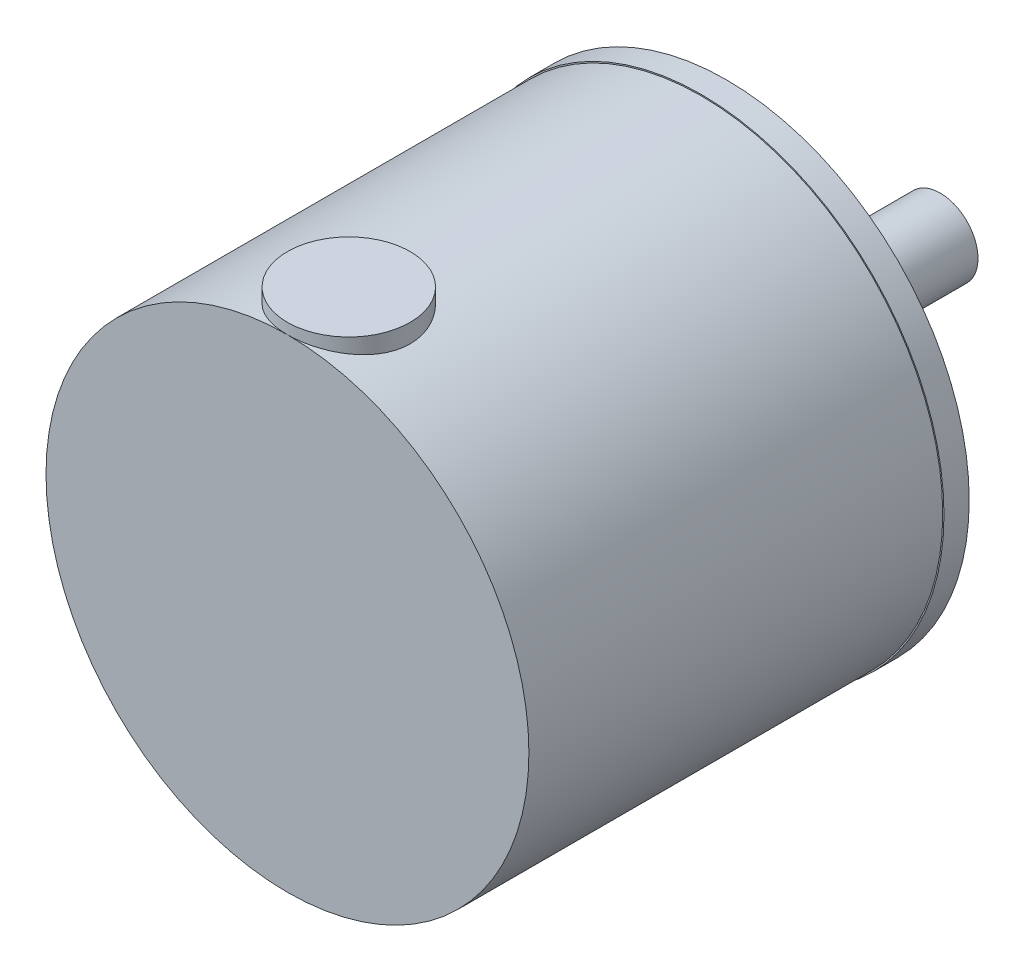
SolidWorks part; units mm, degrees
ref_plane "Alzado" through (0, 0, 0) normal (0, 0, 1) x (1, 0, 0)
ref_plane "Planta" through (0, 0, 0) normal (0, 1, 0) x (1, 0, 0)
ref_plane "Vista lateral" through (0, 0, 0) normal (1, 0, 0) x (0, 0, -1)
sketch "Croquis1" plane through (0, 0, 0) normal (0, 0, 1) x (1, 0, 0)
  circle A0 centre (0, 0) radius 19.15
  dimension "D1" = 38.3
extrude "Saliente-Extruir1" add sketch "Croquis1" along normal blind 34.82
sketch "Croquis2" plane through (0, 0, 0) normal (0, 0, -1) x (-1, 0, 0)
  circle A0 centre (0, 0) radius 9.975
  dimension "D1" = 19.95
extrude "Saliente-Extruir2" add sketch "Croquis2" along normal blind 4.95
sketch "Croquis3" plane through (0, 0, -4.95) normal (0, 0, -1) x (-1, 0, 0)
  line L0 (-1.8393, -2.37) -> (1.8393, -2.37)
  arc A0 (1.8393, -2.37) -> (-1.8393, -2.37) centre (0, 0) ccw
  dimension "D1" = 6
  dimension "D2" = 2.37
extrude "Saliente-Extruir3" add sketch "Croquis3" along normal blind 12
sketch "Croquis4" plane through (0, 0, 0) normal (0, 1, 0) x (1, 0, 0)
  line L0 (-19.15, -34.82) -> (19.15, -34.82) construction
  circle A0 centre (0, -29.955) radius 4.865
  dimension "D1" = 9.73
extrude "Saliente-Extruir4" add sketch "Croquis4" along normal blind 20
sketch "Croquis5" plane through (0, 0, 0) normal (0, 0, -1) x (-1, 0, 0)
  circle A0 centre (0, 0) radius 19.25
  circle A1 centre (0, 0) radius 19.15 construction
  dimension "D1" = 0.1
extrude "Saliente-Extruir5" add sketch "Croquis5" against normal blind 2
sketch "Croquis6" plane through (0, 0, 0) normal (0, 0, -1) x (-1, 0, 0)
  line L0 (-2.6494, -14.1885) -> (13.6123, 4.7998) construction
  line L1 (13.6123, 4.7998) -> (-10.9629, 9.3887) construction
  line L2 (-10.9629, 9.3887) -> (-2.6494, -14.1885) construction
  circle A0 centre (0, 0) radius 14.4338 construction
  circle A1 centre (-10.9629, 9.3887) radius 1.5
  circle A2 centre (13.6123, 4.7998) radius 1.5
  circle A3 centre (-2.6494, -14.1885) radius 1.5
  point P8 (-3.6664, -13.9603)
  point P9 (-2.6494, -14.1885)
  dimension "D1" = 3
  dimension "D2" = 25
extrude "Cortar-Extruir1" cut sketch "Croquis6" against normal blind 5
